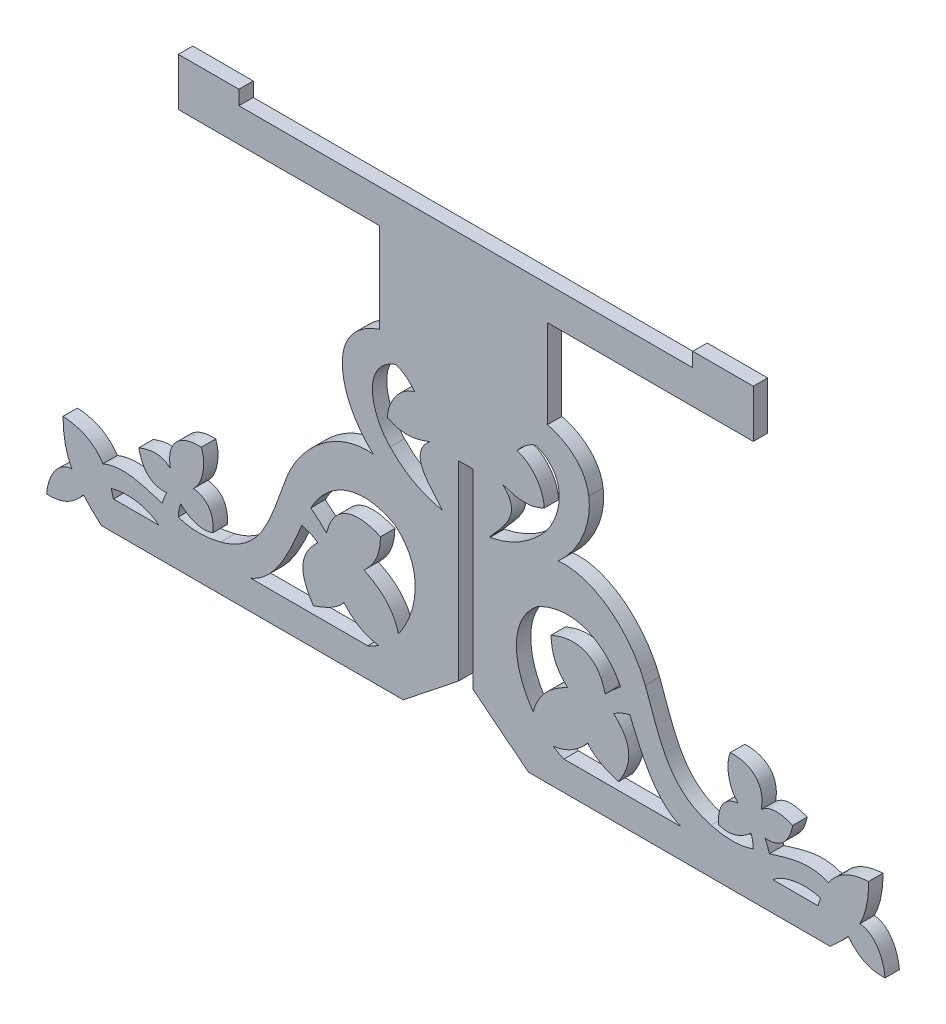
SolidWorks part; units mm, degrees
ref_plane "Plano frontal" through (0, 0, 0) normal (0, 0, 1) x (1, 0, 0)
ref_plane "Plano superior" through (0, 0, 0) normal (0, 1, 0) x (1, 0, 0)
ref_plane "Plano direito" through (0, 0, 0) normal (1, 0, 0) x (0, 0, -1)
sketch "Model" plane through (0, 0, 0) normal (0, 0, 1) x (1, 0, 0)
  line L26 (-12.9004, -101.3152) -> (-12.9004, -88.8288)
  line L27 (-12.9004, -88.8288) -> (-40.9159, -88.8288)
  line L28 (-40.9159, -82.1728) -> (-32.4949, -82.1728)
  line L29 (-32.4949, -82.1728) -> (-32.4949, -84.162)
  line L30 (30.663, -84.162) -> (30.663, -82.1728)
  line L31 (30.663, -82.1728) -> (39.0841, -82.1728)
  line L32 (39.0841, -88.8288) -> (10.4329, -88.8288)
  line L33 (10.4329, -88.8288) -> (10.4329, -101.1372)
  line L34 (49.804, -144.3246) -> (7.7955, -144.3246)
  line L35 (7.7955, -144.3246) -> (0.0841, -138.2088)
  line L36 (0.0841, -138.2088) -> (0.0841, -111.6563)
  line L37 (0.0841, -111.6563) -> (-1.9159, -111.6563)
  line L38 (-1.9159, -111.6563) -> (-1.9159, -138.2088)
  line L39 (-1.9159, -138.2088) -> (-9.6274, -144.3246)
  line L40 (-9.6274, -144.3246) -> (-51.6359, -144.3246)
  line L41 (2.4156, -118.6618) -> (2.4156, -118.7397)
  line L42 (8.893, -104.4415) -> (8.8176, -104.4415)
  line L43 (-4.2475, -118.7397) -> (-4.2475, -118.6619)
  line L44 (-10.6496, -104.4415) -> (-10.7249, -104.4415)
  line L45 (29.0258, -140.2793) -> (12.7362, -140.2793)
  line L46 (48.1117, -140.2793) -> (41.8008, -140.2793)
  line L47 (-30.8577, -140.2793) -> (-14.5681, -140.2793)
  line L48 (-49.9435, -140.2793) -> (-43.6327, -140.2793)
  spline S82 degree 3 poles (-51.6359, -144.3246) (-52.5711, -143.4882) (-53.412, -142.6964) (-54.1351, -141.8668) knots 0 0 0 0 0.016949 0.016949 0.016949 0.016949
  spline S83 degree 3 poles (-54.1351, -141.8668) (-54.1561, -141.8943) (-54.1776, -141.921) (-54.1983, -141.949) knots 0.016949 0.016949 0.016949 0.016949 0.033898 0.033898 0.033898 0.033898
  spline S84 degree 3 poles (-54.1983, -141.949) (-55.7818, -143.8818) (-57.3592, -144.3945) (-59.2492, -144.3247) knots 0.033898 0.033898 0.033898 0.033898 0.050847 0.050847 0.050847 0.050847
  spline S85 degree 3 poles (-59.2492, -144.3247) (-59.046, -141.7372) (-57.5914, -139.63) (-55.7502, -139.5387) knots 0.050847 0.050847 0.050847 0.050847 0.067797 0.067797 0.067797 0.067797
  spline S86 degree 3 poles (-55.7502, -139.5387) (-56.537, -138.0199) (-56.9749, -136.2251) (-56.9668, -133.8269) knots 0.067797 0.067797 0.067797 0.067797 0.084746 0.084746 0.084746 0.084746
  spline S87 degree 3 poles (-56.9668, -133.8269) (-54.4514, -133.9899) (-52.6511, -134.8971) (-51.4058, -136.7659) knots 0.084746 0.084746 0.084746 0.084746 0.101695 0.101695 0.101695 0.101695
  spline S88 degree 3 poles (-51.4058, -136.7659) (-48.5883, -135.5938) (-45.9174, -136.5639) (-43.1636, -137.3933) knots 0.101695 0.101695 0.101695 0.101695 0.118644 0.118644 0.118644 0.118644
  spline S89 degree 3 poles (-43.1636, -137.3933) (-43.0172, -136.8554) (-42.8634, -136.4715) (-42.5318, -135.8202) knots 0.118644 0.118644 0.118644 0.118644 0.135593 0.135593 0.135593 0.135593
  spline S90 degree 3 poles (-42.5318, -135.8202) (-44.9164, -135.9966) (-45.9929, -134.4229) (-46.4211, -132.3417) knots 0.135593 0.135593 0.135593 0.135593 0.152542 0.152542 0.152542 0.152542
  spline S91 degree 3 poles (-46.4211, -132.3417) (-44.684, -131.6994) (-43.3303, -131.5152) (-42.0229, -132.64) knots 0.152542 0.152542 0.152542 0.152542 0.169492 0.169492 0.169492 0.169492
  spline S92 degree 3 poles (-42.0229, -132.64) (-42.6597, -129.2806) (-40.4021, -127.7685) (-37.7166, -127.924) knots 0.169492 0.169492 0.169492 0.169492 0.186441 0.186441 0.186441 0.186441
  spline S93 degree 3 poles (-37.7166, -127.924) (-36.9436, -129.8687) (-37.6542, -132.5106) (-38.8335, -133.46) knots 0.186441 0.186441 0.186441 0.186441 0.20339 0.20339 0.20339 0.20339
  spline S94 degree 3 poles (-38.8335, -133.46) (-36.3102, -133.7397) (-35.9258, -136.0501) (-36.1118, -137.4339) knots 0.20339 0.20339 0.20339 0.20339 0.220339 0.220339 0.220339 0.220339
  spline S95 degree 3 poles (-36.1118, -137.4339) (-37.6366, -137.9979) (-39.2594, -137.4389) (-40.595, -136.1891) knots 0.220339 0.220339 0.220339 0.220339 0.237288 0.237288 0.237288 0.237288
  spline S96 degree 3 poles (-40.595, -136.1891) (-40.7698, -136.588) (-40.9351, -137.367) (-40.9167, -137.933) knots 0.237288 0.237288 0.237288 0.237288 0.254237 0.254237 0.254237 0.254237
  spline S97 degree 3 poles (-40.9167, -137.933) (-39.0959, -138.623) (-36.9839, -138.537) (-35.0344, -138.0166) knots 0.254237 0.254237 0.254237 0.254237 0.271186 0.271186 0.271186 0.271186
  spline S98 degree 3 poles (-35.0344, -138.0166) (-29.072, -136.4249) (-28.0331, -131.4111) (-25.8976, -125.7413) knots 0.271186 0.271186 0.271186 0.271186 0.288136 0.288136 0.288136 0.288136
  spline S99 degree 3 poles (-25.8976, -125.7413) (-24.0243, -120.7679) (-18.9848, -116.2553) (-13.7762, -116.8092) knots 0.288136 0.288136 0.288136 0.288136 0.305085 0.305085 0.305085 0.305085
  spline S100 degree 3 poles (-13.7762, -116.8092) (-17.0224, -113.8641) (-18.4558, -109.9517) (-18.0272, -106.8656) knots 0.305085 0.305085 0.305085 0.305085 0.322034 0.322034 0.322034 0.322034
  spline S101 degree 3 poles (-18.0272, -106.8656) (-17.6224, -103.9501) (-15.3913, -102.1066) (-12.9004, -101.3152) knots 0.322034 0.322034 0.322034 0.322034 0.338983 0.338983 0.338983 0.338983
  spline S102 degree 3 poles (-40.9159, -88.8288) (-40.9159, -86.6101) (-40.9159, -84.3915) (-40.9159, -82.1728) knots 0.372881 0.372881 0.372881 0.372881 0.389831 0.389831 0.389831 0.389831
  spline S103 degree 3 poles (-32.4949, -84.162) (24.9205, -84.162) (-26.7524, -84.162) (30.663, -84.162) knots 0.423729 0.423729 0.423729 0.423729 0.440678 0.440678 0.440678 0.440678
  spline S104 degree 3 poles (39.0841, -82.1728) (39.0841, -84.3915) (39.0841, -86.6101) (39.0841, -88.8288) knots 0.474576 0.474576 0.474576 0.474576 0.491525 0.491525 0.491525 0.491525
  spline S105 degree 3 poles (10.4329, -101.1372) (13.1695, -101.8028) (15.7564, -103.704) (16.1954, -106.8656) knots 0.525424 0.525424 0.525424 0.525424 0.542373 0.542373 0.542373 0.542373
  spline S106 degree 3 poles (16.1954, -106.8656) (16.6239, -109.9517) (15.1905, -113.8641) (11.9443, -116.8092) knots 0.542373 0.542373 0.542373 0.542373 0.559322 0.559322 0.559322 0.559322
  spline S107 degree 3 poles (11.9443, -116.8092) (17.1529, -116.2553) (22.1924, -120.7679) (24.0657, -125.7413) knots 0.559322 0.559322 0.559322 0.559322 0.576271 0.576271 0.576271 0.576271
  spline S108 degree 3 poles (24.0657, -125.7413) (26.2012, -131.4111) (27.2401, -136.4249) (33.2026, -138.0166) knots 0.576271 0.576271 0.576271 0.576271 0.59322 0.59322 0.59322 0.59322
  spline S109 degree 3 poles (33.2026, -138.0166) (35.1521, -138.537) (37.264, -138.623) (39.0848, -137.933) knots 0.59322 0.59322 0.59322 0.59322 0.610169 0.610169 0.610169 0.610169
  spline S110 degree 3 poles (39.0848, -137.933) (39.1033, -137.367) (38.9379, -136.588) (38.7632, -136.1891) knots 0.610169 0.610169 0.610169 0.610169 0.627119 0.627119 0.627119 0.627119
  spline S111 degree 3 poles (38.7632, -136.1891) (37.4275, -137.4389) (35.8047, -137.9979) (34.2799, -137.4339) knots 0.627119 0.627119 0.627119 0.627119 0.644068 0.644068 0.644068 0.644068
  spline S112 degree 3 poles (34.2799, -137.4339) (34.0939, -136.0501) (34.4783, -133.7397) (37.0016, -133.46) knots 0.644068 0.644068 0.644068 0.644068 0.661017 0.661017 0.661017 0.661017
  spline S113 degree 3 poles (37.0016, -133.46) (35.8223, -132.5106) (35.1117, -129.8687) (35.8848, -127.924) knots 0.661017 0.661017 0.661017 0.661017 0.677966 0.677966 0.677966 0.677966
  spline S114 degree 3 poles (35.8848, -127.924) (38.5702, -127.7685) (40.8278, -129.2806) (40.191, -132.64) knots 0.677966 0.677966 0.677966 0.677966 0.694915 0.694915 0.694915 0.694915
  spline S115 degree 3 poles (40.191, -132.64) (41.4985, -131.5152) (42.8521, -131.6994) (44.5892, -132.3417) knots 0.694915 0.694915 0.694915 0.694915 0.711864 0.711864 0.711864 0.711864
  spline S116 degree 3 poles (44.5892, -132.3417) (44.161, -134.4229) (43.0845, -135.9966) (40.6999, -135.8202) knots 0.711864 0.711864 0.711864 0.711864 0.728814 0.728814 0.728814 0.728814
  spline S117 degree 3 poles (40.6999, -135.8202) (41.0315, -136.4715) (41.1853, -136.8554) (41.3317, -137.3933) knots 0.728814 0.728814 0.728814 0.728814 0.745763 0.745763 0.745763 0.745763
  spline S118 degree 3 poles (41.3317, -137.3933) (44.0855, -136.5639) (46.7565, -135.5938) (49.5739, -136.7659) knots 0.745763 0.745763 0.745763 0.745763 0.762712 0.762712 0.762712 0.762712
  spline S119 degree 3 poles (49.5739, -136.7659) (50.8193, -134.8971) (52.6196, -133.9899) (55.135, -133.8269) knots 0.762712 0.762712 0.762712 0.762712 0.779661 0.779661 0.779661 0.779661
  spline S120 degree 3 poles (55.135, -133.8269) (55.1431, -136.2251) (54.7052, -138.0199) (53.9183, -139.5387) knots 0.779661 0.779661 0.779661 0.779661 0.79661 0.79661 0.79661 0.79661
  spline S121 degree 3 poles (53.9183, -139.5387) (55.7595, -139.63) (57.2141, -141.7372) (57.4174, -144.3247) knots 0.79661 0.79661 0.79661 0.79661 0.813559 0.813559 0.813559 0.813559
  spline S122 degree 3 poles (57.4174, -144.3247) (55.5273, -144.3945) (53.9499, -143.8818) (52.3665, -141.949) knots 0.813559 0.813559 0.813559 0.813559 0.830508 0.830508 0.830508 0.830508
  spline S123 degree 3 poles (52.3665, -141.949) (52.3457, -141.921) (52.3243, -141.8943) (52.3032, -141.8668) knots 0.830508 0.830508 0.830508 0.830508 0.847458 0.847458 0.847458 0.847458
  spline S124 degree 3 poles (52.3032, -141.8668) (51.5802, -142.6964) (50.7392, -143.4882) (49.804, -144.3246) knots 0.847458 0.847458 0.847458 0.847458 0.864407 0.864407 0.864407 0.864407
  spline S125 degree 3 poles (2.4156, -118.7397) (5.2833, -118.1337) (7.4563, -116.9728) (9.6195, -114.7647) knots 0.111111 0.111111 0.111111 0.111111 0.222222 0.222222 0.222222 0.222222
  spline S126 degree 3 poles (9.6195, -114.7647) (12.433, -111.8926) (13.6158, -106.2282) (8.893, -104.4415) knots 0.222222 0.222222 0.222222 0.222222 0.333333 0.333333 0.333333 0.333333
  spline S127 degree 3 poles (8.8176, -104.4415) (7.8649, -104.6299) (6.7239, -105.6959) (6.1977, -106.3783) knots 0.444444 0.444444 0.444444 0.444444 0.555556 0.555556 0.555556 0.555556
  spline S128 degree 3 poles (6.1977, -106.3783) (8.3442, -106.9971) (9.9073, -109.2117) (9.9993, -111.4006) knots 0.555556 0.555556 0.555556 0.555556 0.666667 0.666667 0.666667 0.666667
  spline S129 degree 3 poles (9.9993, -111.4006) (7.7737, -112.5166) (5.9614, -112.0782) (4.1652, -111.404) knots 0.666667 0.666667 0.666667 0.666667 0.777778 0.777778 0.777778 0.777778
  spline S130 degree 3 poles (4.1652, -111.404) (7.0946, -114.0167) (4.3185, -116.3971) (2.4156, -118.6618) knots 0.777778 0.777778 0.777778 0.777778 1 1 1 1
  spline S131 degree 3 poles (-4.2475, -118.6619) (-6.1504, -116.3972) (-8.9266, -114.0168) (-5.9971, -111.404) knots 0.111111 0.111111 0.111111 0.111111 0.222222 0.222222 0.222222 0.222222
  spline S132 degree 3 poles (-5.9971, -111.404) (-7.7933, -112.0782) (-9.6056, -112.5166) (-11.8312, -111.4006) knots 0.222222 0.222222 0.222222 0.222222 0.333333 0.333333 0.333333 0.333333
  spline S133 degree 3 poles (-11.8312, -111.4006) (-11.7392, -109.2117) (-10.1761, -106.9971) (-8.0296, -106.3783) knots 0.333333 0.333333 0.333333 0.333333 0.444444 0.444444 0.444444 0.444444
  spline S134 degree 3 poles (-8.0296, -106.3783) (-8.5558, -105.6959) (-9.6968, -104.6299) (-10.6496, -104.4415) knots 0.444444 0.444444 0.444444 0.444444 0.555556 0.555556 0.555556 0.555556
  spline S135 degree 3 poles (-10.7249, -104.4415) (-15.4477, -106.2282) (-14.2649, -111.8926) (-11.4513, -114.7647) knots 0.666667 0.666667 0.666667 0.666667 0.777778 0.777778 0.777778 0.777778
  spline S136 degree 3 poles (-11.4513, -114.7647) (-9.2882, -116.9728) (-7.1152, -118.1337) (-4.2475, -118.7397) knots 0.777778 0.777778 0.777778 0.777778 1 1 1 1
  spline S137 degree 3 poles (9.0006, -123.7822) (13.5481, -121.2633) (18.23, -123.0118) (20.6479, -127.6241) knots 0 0 0 0 0.142857 0.142857 0.142857 0.142857
  spline S138 degree 3 poles (20.6479, -127.6241) (19.8398, -128.2651) (19.0687, -128.9399) (18.4723, -129.5719) knots 0.142857 0.142857 0.142857 0.142857 0.285714 0.285714 0.285714 0.285714
  spline S139 degree 3 poles (18.4723, -129.5719) (17.42, -125.3139) (14.2775, -124.802) (10.9484, -126.2406) knots 0.285714 0.285714 0.285714 0.285714 0.428571 0.428571 0.428571 0.428571
  spline S140 degree 3 poles (10.9484, -126.2406) (11.0149, -128.1564) (11.4719, -129.8168) (13.2598, -131.4102) knots 0.428571 0.428571 0.428571 0.428571 0.571429 0.571429 0.571429 0.571429
  spline S141 degree 3 poles (13.2598, -131.4102) (10.8368, -132.5486) (9.0988, -134.2085) (8.4585, -136.7273) knots 0.571429 0.571429 0.571429 0.571429 0.714286 0.714286 0.714286 0.714286
  spline S142 degree 3 poles (8.4585, -136.7273) (5.7054, -132.8767) (4.8112, -127.1256) (9.0006, -123.7822) knots 0.714286 0.714286 0.714286 0.714286 1 1 1 1
  spline S143 degree 3 poles (11.2295, -139.4825) (13.0658, -139.2201) (14.6921, -138.3655) (16.0476, -136.6912) knots 0 0 0 0 0.125 0.125 0.125 0.125
  spline S144 degree 3 poles (16.0476, -136.6912) (16.831, -137.8892) (18.8371, -138.7799) (20.3087, -139.233) knots 0.125 0.125 0.125 0.125 0.25 0.25 0.25 0.25
  spline S145 degree 3 poles (20.3087, -139.233) (21.9438, -136.7395) (22.7651, -134.182) (19.6643, -131.3158) knots 0.25 0.25 0.25 0.25 0.375 0.375 0.375 0.375
  spline S146 degree 3 poles (19.6643, -131.3158) (20.3829, -130.8576) (21.1444, -130.5259) (21.9025, -130.338) knots 0.375 0.375 0.375 0.375 0.5 0.5 0.5 0.5
  spline S147 degree 3 poles (21.9025, -130.338) (23.4756, -133.9898) (25.265, -138.7339) (29.0258, -140.2793) knots 0.5 0.5 0.5 0.5 0.625 0.625 0.625 0.625
  spline S148 degree 3 poles (12.7362, -140.2793) (12.222, -140.0804) (11.7171, -139.8107) (11.2295, -139.4825) knots 0.75 0.75 0.75 0.75 1 1 1 1
  spline S149 degree 3 poles (48.4363, -139.1712) (48.3192, -139.5215) (48.211, -139.8904) (48.1117, -140.2793) knots 0 0 0 0 0.25 0.25 0.25 0.25
  spline S150 degree 3 poles (41.8008, -140.2793) (43.2247, -139.0671) (45.8993, -138.4201) (48.4363, -139.1712) knots 0.5 0.5 0.5 0.5 1 1 1 1
  spline S151 degree 3 poles (-10.8324, -123.7822) (-15.38, -121.2633) (-20.0618, -123.0118) (-22.4797, -127.6241) knots 0 0 0 0 0.142857 0.142857 0.142857 0.142857
  spline S152 degree 3 poles (-22.4797, -127.6241) (-21.6717, -128.2651) (-20.9005, -128.9399) (-20.3041, -129.5719) knots 0.142857 0.142857 0.142857 0.142857 0.285714 0.285714 0.285714 0.285714
  spline S153 degree 3 poles (-20.3041, -129.5719) (-19.2519, -125.3139) (-16.1094, -124.802) (-12.7803, -126.2406) knots 0.285714 0.285714 0.285714 0.285714 0.428571 0.428571 0.428571 0.428571
  spline S154 degree 3 poles (-12.7803, -126.2406) (-12.8468, -128.1564) (-13.3038, -129.8168) (-15.0917, -131.4102) knots 0.428571 0.428571 0.428571 0.428571 0.571429 0.571429 0.571429 0.571429
  spline S155 degree 3 poles (-15.0917, -131.4102) (-12.6687, -132.5486) (-10.9307, -134.2085) (-10.2904, -136.7273) knots 0.571429 0.571429 0.571429 0.571429 0.714286 0.714286 0.714286 0.714286
  spline S156 degree 3 poles (-10.2904, -136.7273) (-7.5373, -132.8767) (-6.643, -127.1256) (-10.8324, -123.7822) knots 0.714286 0.714286 0.714286 0.714286 1 1 1 1
  spline S157 degree 3 poles (-13.0614, -139.4825) (-14.8977, -139.2201) (-16.524, -138.3655) (-17.8794, -136.6912) knots 0 0 0 0 0.125 0.125 0.125 0.125
  spline S158 degree 3 poles (-17.8794, -136.6912) (-18.6629, -137.8892) (-20.669, -138.7799) (-22.1406, -139.233) knots 0.125 0.125 0.125 0.125 0.25 0.25 0.25 0.25
  spline S159 degree 3 poles (-22.1406, -139.233) (-23.7757, -136.7395) (-24.5969, -134.182) (-21.4962, -131.3158) knots 0.25 0.25 0.25 0.25 0.375 0.375 0.375 0.375
  spline S160 degree 3 poles (-21.4962, -131.3158) (-22.2148, -130.8576) (-22.9763, -130.5259) (-23.7343, -130.338) knots 0.375 0.375 0.375 0.375 0.5 0.5 0.5 0.5
  spline S161 degree 3 poles (-23.7343, -130.338) (-25.3074, -133.9898) (-27.0969, -138.7339) (-30.8577, -140.2793) knots 0.5 0.5 0.5 0.5 0.625 0.625 0.625 0.625
  spline S162 degree 3 poles (-14.5681, -140.2793) (-14.0538, -140.0804) (-13.549, -139.8107) (-13.0614, -139.4825) knots 0.75 0.75 0.75 0.75 1 1 1 1
  spline S163 degree 3 poles (-50.2682, -139.1712) (-50.1511, -139.5215) (-50.0429, -139.8904) (-49.9435, -140.2793) knots 0 0 0 0 0.25 0.25 0.25 0.25
  spline S164 degree 3 poles (-43.6327, -140.2793) (-45.0566, -139.0671) (-47.7312, -138.4201) (-50.2682, -139.1712) knots 0.5 0.5 0.5 0.5 1 1 1 1
extrude "Ressalto-extrusão1" add sketch "Model" along normal blind 2
